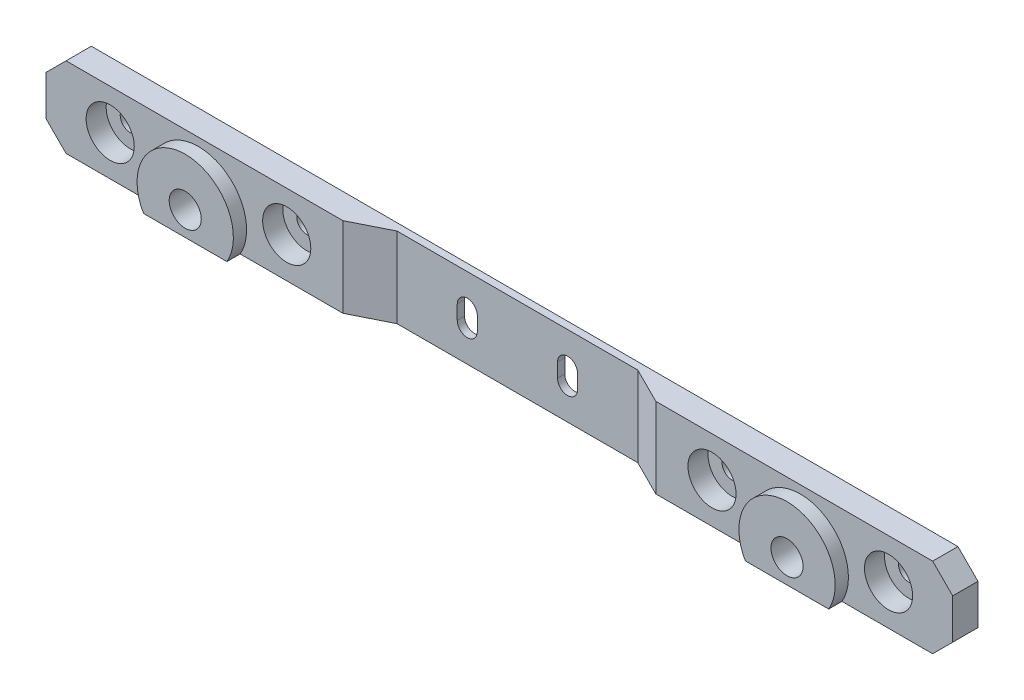
SolidWorks part; units mm, degrees
ref_plane "Front Plane" through (0, 0, 0) normal (0, 0, 1) x (1, 0, 0)
ref_plane "Top Plane" through (0, 0, 0) normal (0, 1, 0) x (1, 0, 0)
ref_plane "Right Plane" through (0, 0, 0) normal (1, 0, 0) x (0, 0, -1)
sketch "Sketch1" plane through (0, 0, 0) normal (0, 0, 1) x (1, 0, 0)
  line L0 (113, 0) -> (113, -20) construction
  line L1 (0, 0) -> (226, 0)
  line L2 (0, 0) -> (0, -20)
  line L3 (0, -20) -> (226, -20)
  line L4 (226, 0) -> (226, -20)
  line L5 (5, 0) -> (0, -5)
  line L6 (0, -15) -> (5, -20)
  line L7 (0, -10) -> (50000, -10) construction
  line L12 (226, -10) -> (-49774, -10) construction
  line L13 (98, -5.75) -> (103, -5.75)
  line L14 (98, -5.75) -> (98, -14.25)
  line L15 (98, -14.25) -> (103, -14.25)
  line L16 (103, -5.75) -> (103, -14.25)
  line L17 (123, -5.75) -> (123, -14.25)
  line L18 (128, -14.25) -> (123, -14.25)
  line L19 (128, -5.75) -> (128, -14.25)
  line L20 (128, -5.75) -> (123, -5.75)
  line L21 (226, -15) -> (221, -20)
  line L22 (221, 0) -> (226, -5)
  line L23 (226, 0) -> (226, -20)
  line L24 (0, -10) -> (50000, -10) construction
  line L25 (226, -10) -> (-49774, -10) construction
  circle A1 centre (16, -10) radius 2.5
  circle A2 centre (60, -10) radius 2.5
  circle A3 centre (100.5, -8.25) radius 2.5
  circle A4 centre (100.5, -11.75) radius 2.5
  circle A5 centre (125.5, -11.75) radius 2.5
  circle A6 centre (125.5, -8.25) radius 2.5
  circle A7 centre (166, -10) radius 2.5
  circle A8 centre (210, -10) radius 2.5
  circle A10 centre (38, -14) radius 4
  circle A11 centre (188, -14) radius 4
  point P13 (0, -10)
  dimension "D7" = 5
  dimension "D13" = 2.5
  dimension "D17" = 8
  dimension "D1" = 226
  dimension "D2" = 20
  dimension "D3" = 5
  dimension "D4" = 5
  dimension "D5" = 5
  dimension "D6" = 5
  dimension "D8" = 16
  dimension "D9" = 44
  dimension "D10" = 98
  dimension "D11" = 5
  dimension "D12" = 8.5
  dimension "D14" = 2.5
  dimension "D15" = 2.5
  dimension "D16" = 2.5
  dimension "D18" = 6
  dimension "D19" = 38
extrude "Boss-Extrude1" add sketch "Sketch1" along normal blind 9.6 contours L22 L1 L5 L2 L6 L3 L21 L4 A7 A2 A1 L20 L19 L18 L17 L13 L16 L15 L14 A8 | A3 L13 L14 | A3 L16 L13 | A4 L15 L16 | L17 A6 L20 | A4 L14 L15 | L20 A6 L19 | L19 A5 L18 | L18 A5 L17
sketch "Sketch2" plane through (0, 0, 9.6) normal (0, 0, 1) x (1, 0, 0)
  line L0 (113, -20) -> (113, 49980) construction
  line L1 (5, -20) -> (221, -20) construction
  line L2 (221, 0) -> (226, -5)
  line L3 (221, 0) -> (226, -5)
  line L4 (226, -5) -> (226, -15)
  line L5 (226, -5) -> (226, -15)
  line L6 (226, -15) -> (221, -20)
  line L7 (226, -15) -> (221, -20)
  line L8 (221, -20) -> (5, -20)
  line L9 (221, -20) -> (5, -20)
  line L10 (5, -20) -> (0, -15)
  line L11 (5, -20) -> (0, -15)
  line L12 (0, -15) -> (0, -5)
  line L13 (0, -15) -> (0, -5)
  line L14 (0, -5) -> (5, 0)
  line L15 (0, -5) -> (5, 0)
  line L16 (5, 0) -> (221, 0)
  line L17 (5, 0) -> (221, 0)
  circle A0 centre (38, -14) radius 12
  circle A1 centre (188, -14) radius 12
  point P7 (113, -20)
  arc M3 (98, -8.25) -> (103, -8.25) centre (100.5, -8.25) cw
  line M4 (103, -8.25) -> (103, -11.75)
  arc M5 (103, -11.75) -> (98, -11.75) centre (100.5, -11.75) cw
  line M6 (98, -11.75) -> (98, -8.25)
  arc M7 (123, -8.25) -> (128, -8.25) centre (125.5, -8.25) cw
  line M8 (128, -8.25) -> (128, -11.75)
  arc M9 (128, -11.75) -> (123, -11.75) centre (125.5, -11.75) cw
  line M10 (123, -11.75) -> (123, -8.25)
  circle M11 centre (210, -10) radius 2.5
  line M12 (226, -5) -> (221, 0)
  line M13 (221, 0) -> (5, 0)
  line M14 (5, 0) -> (0, -5)
  line M15 (0, -5) -> (0, -15)
  line M16 (0, -15) -> (5, -20)
  line M17 (5, -20) -> (221, -20)
  line M18 (221, -20) -> (226, -15)
  line M19 (226, -15) -> (226, -5)
  circle M20 centre (16, -10) radius 2.5
  circle M21 centre (60, -10) radius 2.5
  circle M22 centre (166, -10) radius 2.5
  dimension "D1" = 24
extrude "Cut-Extrude1" cut sketch "Sketch2" against normal blind 3.3 contours L0 L17 A0 M17 M14 M15 M16 M21 M20 M6 M3 M4 M5 | L0 L9 A1 M17 M18 M19 M12 M13 M10 M7 M8 M9 M11 M22
sketch "Sketch4" plane through (0, -20, 0) normal (0, -1, 0) x (1, 0, 0)
  line L0 (113, 6.3) -> (113, 50006.3) construction
  line L1 (48.3923, 6.3) -> (177.6077, 6.3) construction
  line L2 (176, 9.6) -> (199.9997, 9.6)
  line L3 (176, 9.6) -> (199.9997, 9.6)
  line L4 (199.9997, 9.6) -> (199.9997, 6.3)
  line L5 (199.9997, 9.6) -> (199.9997, 6.3)
  line L6 (199.9997, 6.3) -> (221, 6.3)
  line L7 (199.9997, 6.3) -> (221, 6.3)
  line L8 (221, 6.3) -> (226, 6.3)
  line L9 (221, 6.3) -> (226, 6.3)
  line L10 (226, 6.3) -> (226, 0)
  line L11 (226, 6.3) -> (226, 0)
  line L12 (226, 0) -> (221, 0)
  line L13 (226, 0) -> (221, 0)
  line L14 (221, 0) -> (5, 0)
  line L15 (221, 0) -> (5, 0)
  line L16 (5, 0) -> (0, 0)
  line L17 (5, 0) -> (0, 0)
  line L18 (0, 0) -> (0, 6.3)
  line L19 (0, 0) -> (0, 6.3)
  line L20 (0, 6.3) -> (5, 6.3)
  line L21 (0, 6.3) -> (5, 6.3)
  line L22 (5, 6.3) -> (26, 6.3)
  line L23 (5, 6.3) -> (26, 6.3)
  line L24 (26, 6.3) -> (26, 9.6)
  line L25 (26, 6.3) -> (26, 9.6)
  line L26 (26, 9.6) -> (49.9997, 9.6)
  line L27 (26, 9.6) -> (49.9997, 9.6)
  line L28 (49.9997, 9.6) -> (49.9997, 6.3)
  line L29 (49.9997, 9.6) -> (49.9997, 6.3)
  line L30 (49.9997, 6.3) -> (176, 6.3)
  line L31 (49.9997, 6.3) -> (74, 6.3)
  line L32 (176, 6.3) -> (176, 9.6)
  line L33 (176, 6.3) -> (176, 9.6)
  line L34 (200, 14.9584) -> (176.0003, 14.9584)
  line L35 (74, 6.3) -> (83, 1.8)
  line L36 (152, 6.3) -> (176, 6.3)
  line L37 (83, 1.8) -> (143, 1.8)
  line L38 (26, 8.2) -> (49.9997, 8.2)
  line L41 (176.0003, 6.3) -> (152, 6.3)
  line L42 (176.0003, 9.6) -> (176.0003, 6.3)
  line L43 (200, 9.6) -> (176.0003, 9.6)
  line L44 (200, 6.3) -> (200, 9.6)
  line L45 (221, 6.3) -> (200, 6.3)
  line L46 (226, 6.3) -> (221, 6.3)
  line L47 (226, 0) -> (226, 6.3)
  line L48 (221, 0) -> (226, 0)
  line L49 (152, 6.3) -> (176, 6.3)
  line L50 (74, 6.3) -> (50, 6.3)
  line L52 (83, 1.8) -> (143, 1.8)
  line L53 (83, 1.8) -> (143, 1.8)
  line L54 (152, 6.3) -> (143, 1.8)
  line L55 (176.0003, 6.3) -> (152, 6.3)
  line L56 (176.0003, 9.6) -> (176.0003, 6.3)
  line L57 (200, 9.6) -> (176.0003, 9.6)
  line L58 (200, 6.3) -> (200, 9.6)
  point P4 (113, 6.3)
  point P22 (113, 1.8)
  point P27 (113, 1.8)
  point P35 (83, 1.9439)
  dimension "D1" = 74
  dimension "D2" = 1.9
  dimension "D3" = 1.8
  dimension "D7" = 30
extrude "Cut-Extrude2" cut sketch "Sketch4" against normal through all
sketch "Sketch5" plane through (0, 0, 6.3) normal (0, 0, 1) x (1, 0, 0)
  circle A0 centre (16, -10) radius 6
  circle A1 centre (60, -10) radius 6
  circle A2 centre (166, -10) radius 6
  circle A3 centre (210, -10) radius 6
  dimension "D1" = 12
extrude "Cut-Extrude3" cut sketch "Sketch5" against normal blind 5
